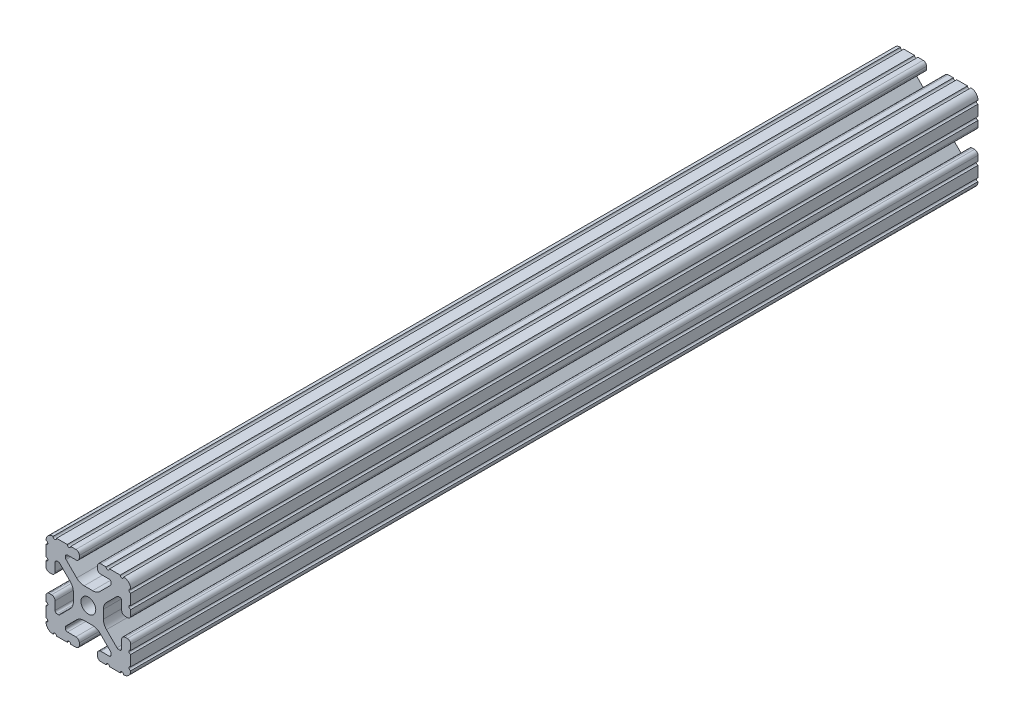
SolidWorks part; units mm, degrees
material "6061 Alloy"
ref_plane "Front Plane" through (0, 0, 0) normal (0, 0, 1) x (1, 0, 0)
ref_plane "Top Plane" through (0, 0, 0) normal (0, 1, 0) x (1, 0, 0)
ref_plane "Right Plane" through (0, 0, 0) normal (1, 0, 0) x (0, 0, -1)
sketch "Sketch1" plane through (0, 0, 0) normal (0, 0, 1) x (1, 0, 0)
  line L0 (0, 25.6181) -> (0, -24.623) construction
  line L1 (-20.8943, 0) -> (20.4607, 0) construction
  line L2 (-10.0229, 12.9148) -> (-5.2522, 8.144)
  line L3 (-10.287, 14.0843) -> (-10.287, 13.5524)
  line L4 (-5.6176, 14.986) -> (-9.3853, 14.986)
  line L5 (-4.064, 17.4964) -> (-4.064, 16.5396)
  line L6 (-7.9742, 19.05) -> (-5.6176, 19.05)
  line L7 (-14.3277, 19.05) -> (-9.4982, 19.05)
  line L8 (-19.05, 9.4961) -> (-19.05, 14.3277)
  line L9 (-19.05, 5.6176) -> (-19.05, 7.9763)
  line L10 (-16.5396, 4.064) -> (-17.4964, 4.064)
  line L11 (-14.986, 9.3853) -> (-14.986, 5.6176)
  line L12 (-13.516, 10.287) -> (-14.0843, 10.287)
  line L13 (-8.1476, 5.2921) -> (-12.8784, 10.0229)
  line L14 (-6.7564, -1.9335) -> (-6.7564, 1.9335)
  line L15 (-12.8784, -10.0229) -> (-8.1476, -5.2921)
  line L16 (-14.0843, -10.287) -> (-13.516, -10.287)
  line L17 (-14.986, -5.6176) -> (-14.986, -9.3853)
  line L18 (-17.4964, -4.064) -> (-16.5396, -4.064)
  line L19 (-19.05, -7.9763) -> (-19.05, -5.6176)
  line L20 (-19.05, -14.3277) -> (-19.05, -9.4961)
  line L21 (-9.4961, -19.05) -> (-14.3277, -19.05)
  line L22 (-5.6176, -19.05) -> (-7.9763, -19.05)
  line L23 (-4.064, -17.4964) -> (-4.064, -16.5396)
  line L24 (10.0229, -12.9148) -> (5.2522, -8.144)
  line L25 (10.287, -14.0843) -> (10.287, -13.5524)
  line L26 (5.6176, -14.986) -> (9.3853, -14.986)
  line L28 (-1.9022, 6.7564) -> (1.9022, 6.7564)
  line L29 (-1.9022, -6.7564) -> (1.9022, -6.7564)
  line L31 (-5.6176, -14.986) -> (-9.3853, -14.986)
  line L32 (-10.287, -14.0843) -> (-10.287, -13.5524)
  line L33 (-10.0229, -12.9148) -> (-5.2522, -8.144)
  line L66 (4.064, -16.5396) -> (4.064, -17.4964)
  line L67 (5.6176, -19.05) -> (7.9763, -19.05)
  line L68 (9.4961, -19.05) -> (14.3277, -19.05)
  line L69 (19.05, -14.3277) -> (19.05, -9.4961)
  line L70 (19.05, -7.9763) -> (19.05, -5.6176)
  line L71 (17.4964, -4.064) -> (16.5396, -4.064)
  line L72 (14.986, -5.6176) -> (14.986, -9.3853)
  line L73 (14.0843, -10.287) -> (13.516, -10.287)
  line L74 (12.8784, -10.0229) -> (8.1476, -5.2921)
  line L75 (6.7564, -1.9335) -> (6.7564, 1.9335)
  line L76 (8.1476, 5.2921) -> (12.8784, 10.0229)
  line L77 (13.516, 10.287) -> (14.0843, 10.287)
  line L78 (14.986, 9.3853) -> (14.986, 5.6176)
  line L79 (16.5396, 4.064) -> (17.4964, 4.064)
  line L80 (19.05, 5.6176) -> (19.05, 7.9763)
  line L81 (19.05, 9.4961) -> (19.05, 14.3277)
  line L82 (14.3277, 19.05) -> (9.4982, 19.05)
  line L83 (7.9742, 19.05) -> (5.6176, 19.05)
  line L84 (4.064, 17.4964) -> (4.064, 16.5396)
  line L85 (5.6176, 14.986) -> (9.3853, 14.986)
  line L86 (10.287, 14.0843) -> (10.287, 13.5524)
  line L87 (10.0229, 12.9148) -> (5.2522, 8.144)
  arc A0 (-10.0229, 12.9148) -> (-10.287, 13.5524) centre (-9.3853, 13.5524) cw
  circle A1 centre (0, 0) radius 3.3274
  arc A2 (-10.287, 14.0843) -> (-9.3853, 14.986) centre (-9.3853, 14.0843) cw
  arc A3 (-4.064, 16.5396) -> (-5.6176, 14.986) centre (-5.6176, 16.5396) cw
  arc A4 (-5.6176, 19.05) -> (-4.064, 17.4964) centre (-5.6176, 17.4964) cw
  arc A5 (-7.9742, 19.05) -> (-9.4982, 19.05) centre (-8.7362, 19.05) cw
  arc A6 (-14.3277, 19.05) -> (-15.8475, 19.05) centre (-15.0876, 18.9933) cw
  arc A7 (-19.05, 15.8475) -> (-15.8475, 19.05) centre (-15.8751, 15.8751) cw
  arc A8 (-19.05, 15.8475) -> (-19.05, 14.3277) centre (-18.9933, 15.0876) cw
  arc A9 (-19.05, 9.4961) -> (-19.05, 7.9763) centre (-18.9933, 8.7362) cw
  arc A10 (-17.4964, 4.064) -> (-19.05, 5.6176) centre (-17.4964, 5.6176) cw
  arc A11 (-14.986, 5.6176) -> (-16.5396, 4.064) centre (-16.5396, 5.6176) cw
  arc A12 (-14.986, 9.3853) -> (-14.0843, 10.287) centre (-14.0843, 9.3853) cw
  arc A13 (-13.516, 10.287) -> (-12.8784, 10.0229) centre (-13.516, 9.3853) cw
  arc A14 (-8.1476, 5.2921) -> (-6.7564, 1.9335) centre (-11.5062, 1.9335) cw
  arc A15 (-6.7564, -1.9335) -> (-8.1476, -5.2921) centre (-11.5062, -1.9335) cw
  arc A16 (-12.8784, -10.0229) -> (-13.516, -10.287) centre (-13.516, -9.3853) cw
  arc A17 (-14.0843, -10.287) -> (-14.986, -9.3853) centre (-14.0843, -9.3853) cw
  arc A18 (-16.5396, -4.064) -> (-14.986, -5.6176) centre (-16.5396, -5.6176) cw
  arc A19 (-19.05, -5.6176) -> (-17.4964, -4.064) centre (-17.4964, -5.6176) cw
  arc A20 (-19.05, -7.9763) -> (-19.05, -9.4961) centre (-18.9933, -8.7362) cw
  arc A21 (-19.05, -14.3277) -> (-19.05, -15.8475) centre (-18.9933, -15.0876) cw
  arc A22 (-15.8475, -19.05) -> (-19.05, -15.8475) centre (-15.8751, -15.8751) cw
  arc A23 (-15.8475, -19.05) -> (-14.3277, -19.05) centre (-15.0876, -18.9933) cw
  arc A24 (-9.4961, -19.05) -> (-7.9763, -19.05) centre (-8.7362, -18.9933) cw
  arc A25 (-4.064, -17.4964) -> (-5.6176, -19.05) centre (-5.6176, -17.4964) cw
  arc A26 (-5.2522, -8.144) -> (-1.9022, -6.7564) centre (-1.9022, -11.494) cw
  arc A27 (1.9022, -6.7564) -> (5.2522, -8.144) centre (1.9022, -11.494) cw
  arc A28 (10.0229, -12.9148) -> (10.287, -13.5524) centre (9.3853, -13.5524) cw
  arc A29 (10.287, -14.0843) -> (9.3853, -14.986) centre (9.3853, -14.0843) cw
  arc A30 (4.064, -16.5396) -> (5.6176, -14.986) centre (5.6176, -16.5396) cw
  arc A31 (-4.064, -16.5396) -> (-5.6176, -14.986) centre (-5.6176, -16.5396) ccw
  arc A32 (-10.287, -14.0843) -> (-9.3853, -14.986) centre (-9.3853, -14.0843) ccw
  arc A33 (-10.0229, -12.9148) -> (-10.287, -13.5524) centre (-9.3853, -13.5524) ccw
  arc A79 (4.064, -17.4964) -> (5.6176, -19.05) centre (5.6176, -17.4964) ccw
  arc A80 (9.4961, -19.05) -> (7.9763, -19.05) centre (8.7362, -18.9933) ccw
  arc A81 (15.8475, -19.05) -> (14.3277, -19.05) centre (15.0876, -18.9933) ccw
  arc A82 (15.8475, -19.05) -> (19.05, -15.8475) centre (15.8751, -15.8751) ccw
  arc A83 (19.05, -14.3277) -> (19.05, -15.8475) centre (18.9933, -15.0876) ccw
  arc A84 (19.05, -7.9763) -> (19.05, -9.4961) centre (18.9933, -8.7362) ccw
  arc A85 (19.05, -5.6176) -> (17.4964, -4.064) centre (17.4964, -5.6176) ccw
  arc A86 (16.5396, -4.064) -> (14.986, -5.6176) centre (16.5396, -5.6176) ccw
  arc A87 (14.0843, -10.287) -> (14.986, -9.3853) centre (14.0843, -9.3853) ccw
  arc A88 (12.8784, -10.0229) -> (13.516, -10.287) centre (13.516, -9.3853) ccw
  arc A89 (6.7564, -1.9335) -> (8.1476, -5.2921) centre (11.5062, -1.9335) ccw
  arc A90 (8.1476, 5.2921) -> (6.7564, 1.9335) centre (11.5062, 1.9335) ccw
  arc A91 (13.516, 10.287) -> (12.8784, 10.0229) centre (13.516, 9.3853) ccw
  arc A92 (14.986, 9.3853) -> (14.0843, 10.287) centre (14.0843, 9.3853) ccw
  arc A93 (14.986, 5.6176) -> (16.5396, 4.064) centre (16.5396, 5.6176) ccw
  arc A94 (17.4964, 4.064) -> (19.05, 5.6176) centre (17.4964, 5.6176) ccw
  arc A95 (19.05, 9.4961) -> (19.05, 7.9763) centre (18.9933, 8.7362) ccw
  arc A96 (19.05, 15.8475) -> (19.05, 14.3277) centre (18.9933, 15.0876) ccw
  arc A97 (19.05, 15.8475) -> (15.8475, 19.05) centre (15.8751, 15.8751) ccw
  arc A98 (14.3277, 19.05) -> (15.8475, 19.05) centre (15.0876, 18.9933) ccw
  arc A99 (7.9742, 19.05) -> (9.4982, 19.05) centre (8.7362, 19.05) ccw
  arc A100 (5.6176, 19.05) -> (4.064, 17.4964) centre (5.6176, 17.4964) ccw
  arc A101 (4.064, 16.5396) -> (5.6176, 14.986) centre (5.6176, 16.5396) ccw
  arc A102 (10.287, 14.0843) -> (9.3853, 14.986) centre (9.3853, 14.0843) ccw
  arc A103 (10.0229, 12.9148) -> (10.287, 13.5524) centre (9.3853, 13.5524) ccw
  arc A104 (1.9022, 6.7564) -> (5.2522, 8.144) centre (1.9022, 11.494) ccw
  arc A105 (-5.2522, 8.144) -> (-1.9022, 6.7564) centre (-1.9022, 11.494) ccw
  dimension "D1" = 6.6548
  dimension "D2" = 19.05
  dimension "D3" = 38.1
  dimension "D4" = 20.574
  dimension "D5" = 13.5128
  dimension "D6" = 4.064
  dimension "D7" = 8.128
  dimension "D8" = 4.064
  dimension "D9" = 12.2936
extrude "Extrude1" add sketch "Sketch1" against normal blind 381
